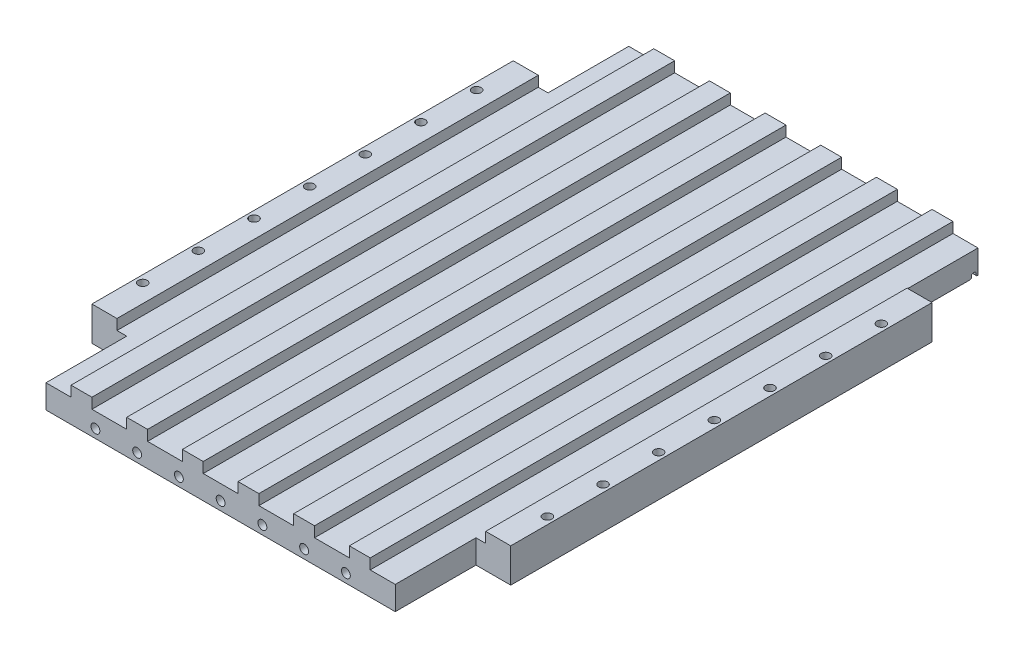
SolidWorks part; units mm, degrees
material "ABS"
ref_plane "Front Plane" through (0, 0, 0) normal (0, 0, 1) x (1, 0, 0)
ref_plane "Top Plane" through (0, 0, 0) normal (0, 1, 0) x (1, 0, 0)
ref_plane "Right Plane" through (0, 0, 0) normal (1, 0, 0) x (0, 0, -1)
sketch "Sketch1" plane through (0, 0, 0) normal (0, 1, 0) x (1, 0, 0)
  line L1 (0, 0) -> (76.454, 0)
  line L2 (0, 0) -> (0, 106.3752)
  line L3 (0, 106.3752) -> (76.454, 106.3752)
  line L4 (76.454, 0) -> (76.454, 106.3752)
  dimension "D1" = 106.3752
  dimension "D2" = 76.454
extrude "Extrude1" add sketch "Sketch1" against normal blind 6.223
sketch "Sketch2" plane through (0, 0, 0) normal (0, 1, 0) x (-1, 0, 0)
  line L0 (-38.227, 0) -> (0, 0) construction
  line L1 (0, 0) -> (-76.454, 0) construction
  line L2 (-38.227, 0) -> (-38.227, -106.3752) construction
  line L3 (0, 0) -> (-6.35, 0)
  line L4 (0, 0) -> (0, -14.732)
  line L5 (0, -14.732) -> (-6.35, -14.732)
  line L6 (-6.35, 0) -> (-6.35, -14.732)
  line L7 (-76.454, -106.3752) -> (0, -106.3752) construction
  line L8 (-70.104, 0) -> (-70.104, -14.732)
  line L9 (-76.454, -14.732) -> (-70.104, -14.732)
  line L10 (-76.454, 0) -> (-76.454, -14.732)
  line L11 (-76.454, 0) -> (-70.104, 0)
  line L12 (0, -53.1876) -> (-76.454, -53.1876) construction
  line L13 (0, -106.3752) -> (0, 0) construction
  line L14 (-76.454, 0) -> (-76.454, -106.3752) construction
  line L15 (-76.454, -106.3752) -> (-70.104, -106.3752)
  line L16 (-76.454, -106.3752) -> (-76.454, -91.6432)
  line L17 (-76.454, -91.6432) -> (-70.104, -91.6432)
  line L18 (-70.104, -106.3752) -> (-70.104, -91.6432)
  line L19 (-6.35, -106.3752) -> (-6.35, -91.6432)
  line L20 (0, -91.6432) -> (-6.35, -91.6432)
  line L21 (0, -106.3752) -> (0, -91.6432)
  line L22 (0, -106.3752) -> (-6.35, -106.3752)
  dimension "D1" = 14.732
  dimension "D2" = 6.35
extrude "Extrude2" cut sketch "Sketch2" against normal through all
sketch "Sketch3" plane through (0, 0, 0) normal (0, 0, 1) x (1, 0, 0)
  line L1 (6.35, -6.223) -> (70.104, -6.223) construction
  line L2 (15.367, -4.6355) -> (22.987, -4.6355) construction
  line L3 (22.987, -4.6355) -> (30.607, -4.6355) construction
  line L4 (30.607, -4.6355) -> (38.227, -4.6355) construction
  line L5 (38.227, -4.6355) -> (45.847, -4.6355) construction
  line L6 (45.847, -4.6355) -> (53.467, -4.6355) construction
  line L7 (53.467, -4.6355) -> (61.087, -4.6355) construction
  circle A0 centre (38.227, -4.6355) radius 0.8128
  circle A1 centre (45.847, -4.6355) radius 0.8128
  circle A2 centre (53.467, -4.6355) radius 0.8128
  circle A3 centre (61.087, -4.6355) radius 0.8128
  circle A4 centre (30.607, -4.6355) radius 0.8128
  circle A5 centre (38.227, -4.6355) radius 0.8128
  circle A6 centre (45.847, -4.6355) radius 0.8128
  circle A7 centre (53.467, -4.6355) radius 0.8128
  circle A8 centre (22.987, -4.6355) radius 0.8128
  circle A9 centre (30.607, -4.6355) radius 0.8128
  circle A10 centre (38.227, -4.6355) radius 0.8128
  circle A11 centre (45.847, -4.6355) radius 0.8128
  circle A12 centre (15.367, -4.6355) radius 0.8128
  circle A13 centre (22.987, -4.6355) radius 0.8128
  circle A14 centre (30.607, -4.6355) radius 0.8128
  circle A15 centre (38.227, -4.6355) radius 0.8128
  dimension "D1" = 1.5875
extrude "Extrude3" cut sketch "Sketch3" against normal blind 9.525 contours A12 | A8 | A4 | A0 | A1 | A2 | A3
sketch "Sketch5" plane through (0, 0, 0) normal (0, 1, 0) x (1, 0, 0)
  line L0 (0, 106.3752) -> (0, 53.1876) construction
  line L1 (0, 91.6432) -> (0, 14.732) construction
  line L2 (0, 53.1876) -> (2.5781, 53.1876) construction
  line L3 (0, 91.6432) -> (0, 106.3752) construction
  line L4 (6.35, 106.3752) -> (0, 106.3752) construction
  line L5 (38.227, 106.3752) -> (38.227, 0) construction
  line L6 (70.104, 106.3752) -> (6.35, 106.3752) construction
  line L7 (6.35, 0) -> (70.104, 0) construction
  circle A0 centre (1.2891, 53.1876) radius 0.8128
  circle A1 centre (1.289, 63.3476) radius 0.8128
  circle A2 centre (1.289, 73.5076) radius 0.8128
  circle A3 centre (1.289, 83.6676) radius 0.8128
  circle A4 centre (1.2891, 43.0276) radius 0.8128
  circle A5 centre (1.2891, 53.1876) radius 0.8128
  circle A6 centre (1.2891, 63.3476) radius 0.8128
  circle A7 centre (1.2891, 73.5076) radius 0.8128
  circle A8 centre (1.2891, 32.8676) radius 0.8128
  circle A9 centre (1.2891, 43.0276) radius 0.8128
  circle A10 centre (1.2891, 53.1876) radius 0.8128
  circle A11 centre (1.2891, 63.3476) radius 0.8128
  circle A12 centre (1.2891, 22.7076) radius 0.8128
  circle A13 centre (1.2891, 32.8676) radius 0.8128
  circle A14 centre (1.2891, 43.0276) radius 0.8128
  circle A15 centre (1.2891, 53.1876) radius 0.8128
  circle A16 centre (75.1649, 53.1876) radius 0.8128
  circle A17 centre (75.1649, 43.0276) radius 0.8128
  circle A18 centre (75.1649, 32.8676) radius 0.8128
  circle A19 centre (75.1649, 22.7076) radius 0.8128
  circle A20 centre (75.1649, 63.3476) radius 0.8128
  circle A21 centre (75.1649, 53.1876) radius 0.8128
  circle A22 centre (75.1649, 43.0276) radius 0.8128
  circle A23 centre (75.1649, 32.8676) radius 0.8128
  circle A24 centre (75.1649, 73.5076) radius 0.8128
  circle A25 centre (75.1649, 63.3476) radius 0.8128
  circle A26 centre (75.1649, 53.1876) radius 0.8128
  circle A27 centre (75.1649, 43.0276) radius 0.8128
  circle A28 centre (75.165, 83.6676) radius 0.8128
  circle A29 centre (75.1649, 73.5076) radius 0.8128
  circle A30 centre (75.1649, 63.3476) radius 0.8128
  circle A31 centre (75.1649, 53.1876) radius 0.8128
extrude "Extrude4" cut sketch "Sketch5" against normal through all contours A3 | A1 | A0 | A2 | A8 | A12 | A28 | A24 | A20 | A16 | A17 | A18 | A19 | A4
sketch "Sketch7" plane through (0, -6.223, 0) normal (0, -1, 0) x (1, 0, 0)
  line L2 (6.35, -91.6432) -> (6.35, -106.3752) construction
  line L3 (6.35, -105.5878) -> (70.104, -105.5878) construction
  line L4 (70.104, -106.3752) -> (70.104, -91.6432) construction
  line L5 (70.104, -105.9847) -> (6.35, -105.9847)
  line L6 (70.104, -105.9847) -> (70.104, -105.1909)
  line L7 (70.104, -105.1909) -> (6.35, -105.1909)
  line L8 (6.35, -105.9847) -> (6.35, -105.1909)
  line L9 (70.104, -105.9847) -> (6.35, -105.1909) construction
  line L10 (70.104, -105.1909) -> (6.35, -105.9847) construction
  point P0 (38.227, -105.5878)
  dimension "D1" = 0.7937
extrude "Extrude5" cut sketch "Sketch7" against normal blind 0.7937
chamfer "Chamfer1" distance 0.1778 angle 45 4 edges at (38.227, -5.4292, -105.1909) (38.227, -5.4292, -105.9847) (38.227, -6.223, -105.1909) (38.227, -6.223, -105.9847)
sketch "Sketch8" plane through (0, 0, 0) normal (0, 1, 0) x (-1, 0, 0)
  line L2 (-6.35, 0) -> (-70.104, 0) construction
  line L3 (-24.892, -106.3752) -> (-31.242, -106.3752)
  line L4 (-35.052, -106.3752) -> (-41.402, -106.3752)
  line L5 (-35.052, -106.3752) -> (-35.052, 0)
  line L6 (-35.052, 0) -> (-41.402, 0)
  line L7 (-41.402, -106.3752) -> (-41.402, 0)
  line L8 (-35.052, -106.3752) -> (-41.402, 0) construction
  line L9 (-35.052, 0) -> (-41.402, -106.3752) construction
  line L10 (-24.892, -106.3752) -> (-24.892, 0)
  line L11 (-31.242, -106.3752) -> (-31.242, 0)
  line L12 (-24.892, 0) -> (-31.242, 0)
  line L13 (-14.732, -106.3752) -> (-21.082, -106.3752)
  line L14 (-14.732, -106.3752) -> (-14.732, 0)
  line L15 (-21.082, -106.3752) -> (-21.082, 0)
  line L16 (-14.732, 0) -> (-21.082, 0)
  line L17 (-4.572, -106.3752) -> (-10.922, -106.3752)
  line L18 (-4.572, -106.3752) -> (-4.572, 0)
  line L19 (-10.922, -106.3752) -> (-10.922, 0)
  line L20 (-4.572, 0) -> (-10.922, 0)
  line L21 (-45.212, -106.3752) -> (-51.562, -106.3752)
  line L22 (-45.212, -106.3752) -> (-45.212, 0)
  line L23 (-51.562, -106.3752) -> (-51.562, 0)
  line L24 (-45.212, 0) -> (-51.562, 0)
  line L25 (-35.052, -106.3752) -> (-41.402, -106.3752)
  line L26 (-35.052, -106.3752) -> (-35.052, 0)
  line L27 (-41.402, -106.3752) -> (-41.402, 0)
  line L28 (-35.052, 0) -> (-41.402, 0)
  line L29 (-24.892, -106.3752) -> (-31.242, -106.3752)
  line L30 (-24.892, -106.3752) -> (-24.892, 0)
  line L31 (-31.242, -106.3752) -> (-31.242, 0)
  line L32 (-24.892, 0) -> (-31.242, 0)
  line L33 (-14.732, -106.3752) -> (-21.082, -106.3752)
  line L34 (-14.732, -106.3752) -> (-14.732, 0)
  line L35 (-21.082, -106.3752) -> (-21.082, 0)
  line L36 (-14.732, 0) -> (-21.082, 0)
  line L37 (-55.372, -106.3752) -> (-61.722, -106.3752)
  line L38 (-55.372, -106.3752) -> (-55.372, 0)
  line L39 (-61.722, -106.3752) -> (-61.722, 0)
  line L40 (-55.372, 0) -> (-61.722, 0)
  line L41 (-45.212, -106.3752) -> (-51.562, -106.3752)
  line L42 (-45.212, -106.3752) -> (-45.212, 0)
  line L43 (-51.562, -106.3752) -> (-51.562, 0)
  line L44 (-45.212, 0) -> (-51.562, 0)
  line L45 (-35.052, -106.3752) -> (-41.402, -106.3752)
  line L46 (-35.052, -106.3752) -> (-35.052, 0)
  line L47 (-41.402, -106.3752) -> (-41.402, 0)
  line L48 (-35.052, 0) -> (-41.402, 0)
  line L49 (-24.892, -106.3752) -> (-31.242, -106.3752)
  line L50 (-24.892, -106.3752) -> (-24.892, 0)
  line L51 (-31.242, -106.3752) -> (-31.242, 0)
  line L52 (-24.892, 0) -> (-31.242, 0)
  line L53 (-65.532, -106.3752) -> (-71.882, -106.3752)
  line L54 (-65.532, -106.3752) -> (-65.532, 0)
  line L55 (-71.882, -106.3752) -> (-71.882, 0)
  line L56 (-65.532, 0) -> (-71.882, 0)
  line L57 (-55.372, -106.3752) -> (-61.722, -106.3752)
  line L58 (-55.372, -106.3752) -> (-55.372, 0)
  line L59 (-61.722, -106.3752) -> (-61.722, 0)
  line L60 (-55.372, 0) -> (-61.722, 0)
  line L61 (-45.212, -106.3752) -> (-51.562, -106.3752)
  line L62 (-45.212, -106.3752) -> (-45.212, 0)
  line L63 (-51.562, -106.3752) -> (-51.562, 0)
  line L64 (-45.212, 0) -> (-51.562, 0)
  line L65 (-35.052, -106.3752) -> (-41.402, -106.3752)
  line L66 (-35.052, -106.3752) -> (-35.052, 0)
  line L67 (-41.402, -106.3752) -> (-41.402, 0)
  line L68 (-35.052, 0) -> (-41.402, 0)
  point P6 (-38.227, -53.1876)
  line M5 (-70.104, -106.3752) -> (-6.35, -106.3752)
  line M6 (-6.35, -106.3752) -> (-6.35, -91.6432)
  line M7 (-6.35, -91.6432) -> (0, -91.6432)
  line M9 (0, -14.732) -> (-6.35, -14.732)
  line M10 (-6.35, -14.732) -> (-6.35, 0)
  line M11 (-6.35, 0) -> (-70.104, 0)
  line M12 (-70.104, 0) -> (-70.104, -14.732)
  line M13 (-70.104, -14.732) -> (-76.454, -14.732)
  line M15 (-76.454, -91.6432) -> (-70.104, -91.6432)
  line M16 (-70.104, -91.6432) -> (-70.104, -106.3752)
  dimension "D1" = 6.35
extrude "Extrude7" cut sketch "Sketch8" against normal blind 1.905 contours L19 L18 M5 M6 M7 M9 M10 M11 | L15 L14 M5 M11 | L11 L10 M5 M11 | L7 L5 M5 M11 | L39 L38 M5 M11 | L55 L54 M15 M16 M5 M11 M12 M13 | L23 L22 M5 M11
